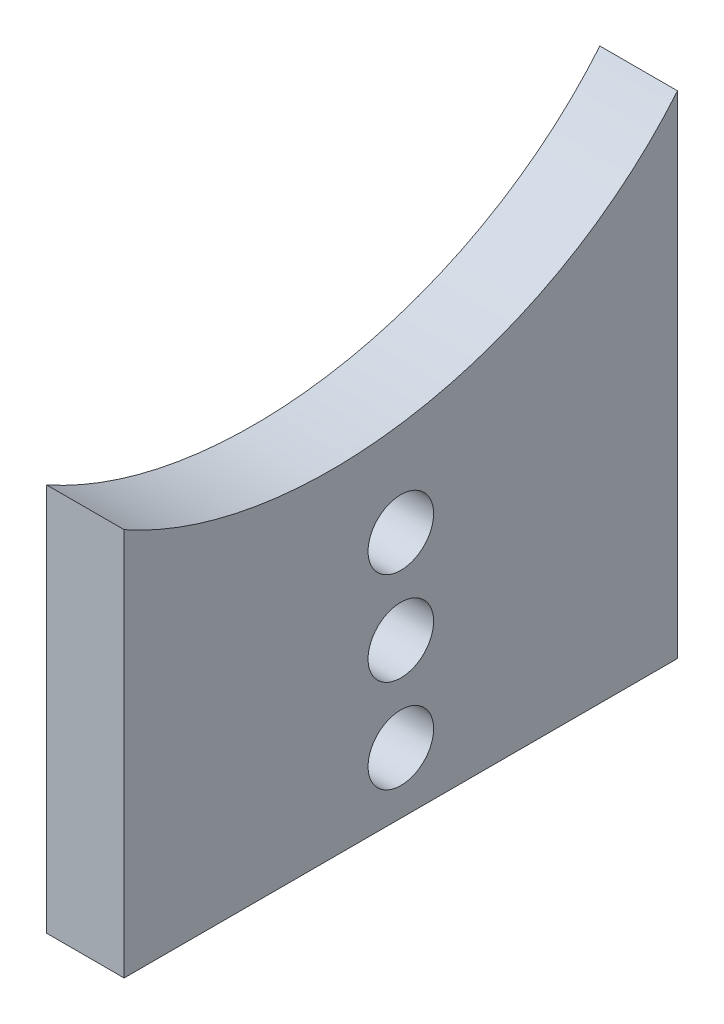
SolidWorks part; units mm, degrees
ref_plane "Front" through (0, 0, 0) normal (0, 0, 1) x (1, 0, 0)
ref_plane "Top" through (0, 0, 0) normal (0, 1, 0) x (1, 0, 0)
ref_plane "Right" through (0, 0, 0) normal (1, 0, 0) x (0, 0, -1)
sketch "Sketch1" plane through (0, 0, 0) normal (1, 0, 0) x (0, 0, -1)
  line L0 (-29.0526, -0.1655) -> (-29.0526, -50.1655)
  line L1 (42.2104, 13.1426) -> (42.2104, -50.1655)
  line L2 (42.2104, -50.1655) -> (-29.0526, -50.1655)
  circle A0 centre (6.5789, -42.2971) radius 4.2218
  circle A1 centre (6.5789, -30.2971) radius 4.2218
  circle A2 centre (6.5789, -18.2971) radius 4.2218
  spline S0 degree 3 poles (-29.0526, -0.1655) (-6.5, -12.7748) (25.4277, -7.095) (42.2104, 13.1426) knots 0 0 0 0 1 1 1 1
  dimension "D1" = 50
  dimension "D2" = 63.3081
  dimension "D3" = 12
  dimension "D4" = 12
extrude "Boss-Extrude1" add sketch "Sketch1" along normal blind 10
